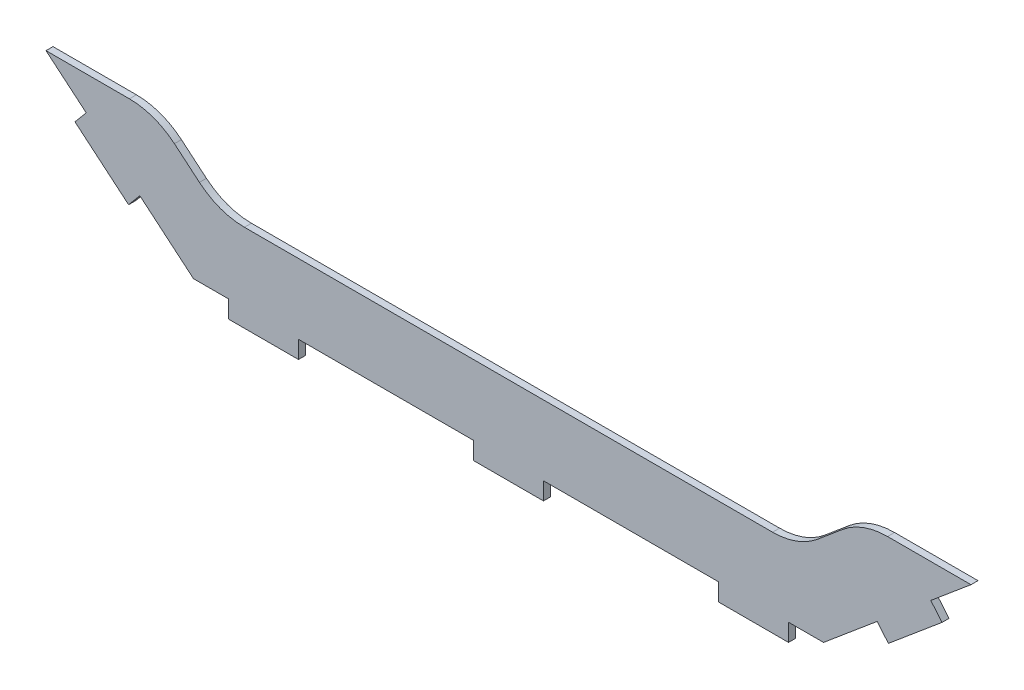
SolidWorks part; units mm, degrees
material "PBT General Purpose"
ref_plane "Front Plane" through (0, 0, 0) normal (0, 0, 1) x (1, 0, 0)
ref_plane "Top Plane" through (0, 0, 0) normal (0, 1, 0) x (1, 0, 0)
ref_plane "Right Plane" through (0, 0, 0) normal (1, 0, 0) x (0, 0, -1)
sketch "frame_outline" plane through (0, 0, 0) normal (0, 0, 1) x (1, 0, 0)
  line L89 (0.5, 0) -> (3, 0)
  line L99 (3, 0) -> (3, -0.25)
  line L100 (3, -0.25) -> (4, -0.25)
  line L101 (4, -0.25) -> (4, 0)
  line L102 (4, 0) -> (4.5, 0)
  line L103 (4.5, 0) -> (5.266, 0.6428)
  line L104 (5.266, 0.6428) -> (5.4267, 0.4513)
  line L105 (5.4267, 0.4513) -> (6.1928, 1.0941)
  line L106 (6.1928, 1.0941) -> (6.0321, 1.2856)
  line L107 (6.0321, 1.2856) -> (6.6066, 1.7677)
  line L108 (6.6066, 1.7677) -> (5.0509, 1.7677)
  line L109 (5.0509, 1.7677) -> (4.136, 1)
  line L110 (4.136, 1) -> (-4.136, 1)
  line L111 (-0.5, 0) -> (-3, 0)
  line L112 (-3, 0) -> (-3, -0.25)
  line L113 (-3, -0.25) -> (-4, -0.25)
  line L114 (-4, -0.25) -> (-4, 0)
  line L115 (-4, 0) -> (-4.5, 0)
  line L116 (-4.5, 0) -> (-5.266, 0.6428)
  line L117 (-5.266, 0.6428) -> (-5.4267, 0.4513)
  line L118 (-5.4267, 0.4513) -> (-6.1928, 1.0941)
  line L119 (-6.1928, 1.0941) -> (-6.0321, 1.2856)
  line L120 (-6.0321, 1.2856) -> (-6.6066, 1.7677)
  line L121 (-6.6066, 1.7677) -> (-5.0509, 1.7677)
  line L122 (-5.0509, 1.7677) -> (-4.136, 1)
  line L123 (-0.5, 0) -> (-0.5, -0.25)
  line L124 (-0.5, -0.25) -> (0.5, -0.25)
  line L125 (0.5, -0.25) -> (0.5, 0)
  point P0 (0, -0.25)
  dimension "D2" = 1
  dimension "D3" = 0.5
  dimension "D4" = 1
  dimension "D5" = 0.25
  dimension "D6" = 0.25
  dimension "D7" = 0.25
  dimension "D8" = 140
  dimension "D9" = 1
  dimension "D10" = 140
  dimension "D11" = 1
  dimension "D12" = 0.75
  dimension "D13" = 1
  dimension "D14" = 1
  dimension "D15" = 3
  dimension "D16" = 1
  dimension "D17" = 0.25
  dimension "D18" = 3
extrude "Boss-Extrude1" add sketch "frame_outline" along normal mid plane 0.1 contours L89 L99 L100 L101 L102 L103 L104 L105 L106 L107 L108 L109 L110 L122 L121 L120 L119 L118 L117 L116 L115 L114 L113 L112 L111 L123 L124 L125
fillet "Fillet1" radius 1 4 edges at (4.136, 1, 0) (5.0509, 1.7677, 0) (-4.136, 1, 0) (-5.0509, 1.7677, 0)
equation "\"t\"= 0.25'thickness of the sheets"
equation "\"t_cf\"= 0.115'thickness of single carbon fiber layer"
equation "\"t_kapton\"= 0.025'thickness of single Kapton flex layer"
equation "\"t_fr4\"= 0.1'thickness of FR4 with copper layer"
equation "\"joint_flex\"= 0.1'Width of flextures gap"
equation "\"joint_flex_eff\"= 0.02'Width of flecture after castelation"
equation "\"joint_fold\"= 0.2'Width of folding joints for 90deg fold"
equation "\"gap_tolerance\"= 0.002'Width to have interfecence fit between carbon fiber inserts"
equation "\"assemble_angle\"= 90'Angle of assembly parts"
equation "\"D1@Boss-Extrude1\"=0.1"
equation "\"link_lift\"= 0.5'Actuation linkage amplification for the lift motion"
equation "\"link_swing\"= 0.45'Actuation linkage amplification for the swing motion"
